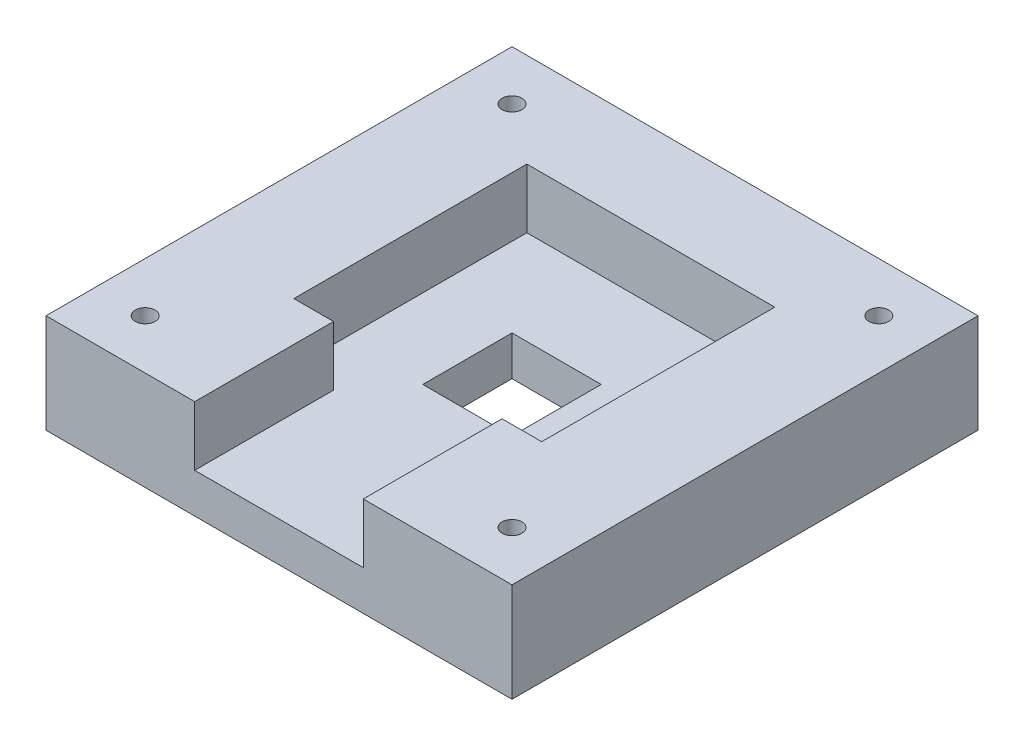
SolidWorks part; units mm, degrees
ref_plane "Front Plane" through (0, 0, 0) normal (0, 0, 1) x (1, 0, 0)
ref_plane "Top Plane" through (0, 0, 0) normal (0, 1, 0) x (1, 0, 0)
ref_plane "Right Plane" through (0, 0, 0) normal (1, 0, 0) x (0, 0, -1)
sketch "Sketch1" plane through (0, 0, 0) normal (0, 1, 0) x (1, 0, 0)
  line L1 (0, 0) -> (47, 0)
  line L2 (0, 0) -> (0, -47)
  line L3 (0, -47) -> (47, -47)
  line L4 (47, 0) -> (47, -47)
  dimension "D1" = 47
  dimension "D2" = 47
extrude "Boss-Extrude1" add sketch "Sketch1" along normal blind 10
sketch "Sketch2" plane through (0, 0, 0) normal (0, -1, 0) x (-1, 0, 0)
  line L0 (0, -47) -> (-47, -47) construction
  line L1 (-28, -19) -> (-19, -19)
  line L2 (-28, -19) -> (-28, -28)
  line L3 (-28, -28) -> (-19, -28)
  line L4 (-19, -19) -> (-19, -28)
  line L5 (-47, -47) -> (-47, 0) construction
  dimension "D1" = 9
  dimension "D2" = 9
  dimension "D3" = 19
  dimension "D4" = 19
extrude "Cut-Extrude1" cut sketch "Sketch2" against normal blind 4
sketch "Sketch5" plane through (0, 0, 0) normal (0, -1, 0) x (-1, 0, 0)
  line L0 (-28, -28) -> (-19, -28) construction
  line L1 (-36, -9.5) -> (-11, -9.5)
  line L2 (-36, -9.5) -> (-36, -33)
  line L3 (-36, -33) -> (-11, -33)
  line L4 (-11, -9.5) -> (-11, -33)
  line L5 (-19, -28) -> (-19, -19) construction
  line L6 (0, -47) -> (-47, -47) construction
  line L7 (-32, -33) -> (-15, -33)
  line L8 (-32, -33) -> (-32, -47)
  line L9 (-32, -47) -> (-15, -47)
  line L10 (-15, -33) -> (-15, -47)
  dimension "D1" = 5
  dimension "D2" = 8
  dimension "D3" = 23.5
  dimension "D4" = 25
  dimension "D5" = 4
  dimension "D6" = 4
sketch3d "3DSketch1"
  line L0 (36, 0, 9.5) -> (36, 0, 33) construction
  line L1 (36, 4, 9.5) -> (11, 4, 9.5)
  line L2 (36, 4, 9.5) -> (36, 4, 33)
  line L3 (36, 4, 33) -> (11, 4, 33)
  line L4 (11, 4, 9.5) -> (11, 4, 33)
  line L5 (32, 4, 33) -> (15, 4, 33)
  line L6 (32, 4, 33) -> (32, 4, 47)
  line L7 (32, 4, 47) -> (15, 4, 47)
  line L8 (15, 4, 33) -> (15, 4, 47)
  line L9 (11, 0, 9.5) -> (11, 0, 33) construction
  line L10 (36, 0, 33) -> (11, 0, 33) construction
  line L11 (32, 0, 33) -> (32, 0, 47) construction
  line L12 (15, 0, 33) -> (15, 0, 47) construction
  line L13 (32, 0, 47) -> (15, 0, 47) construction
  point P8 (36, 4, 21.25)
  dimension "D1" = 4
  dimension "D2" = 25
  dimension "D3" = 23.5
  dimension "D4" = 4
  dimension "D5" = 4
  dimension "D6" = 4
  dimension "D7" = 4
  dimension "D8" = 4
  dimension "D9" = 4
extrude "Cut-Extrude3" cut sketch "3DSketch1" along direction (0, 1, 0) on the side against the normal through all contours L1 L4 L3 L2 | L6 L7 L8 L5
sketch "Sketch8" plane through (0, 0, 0) normal (0, -1, 0) x (1, 0, 0)
  line L0 (47, 0) -> (0, 0) construction
  line L1 (47, 47) -> (47, 0) construction
  line L2 (0, 0) -> (0, 47) construction
  line L3 (0, 47) -> (47, 47) construction
  circle A0 centre (42, 5) radius 1
  circle A1 centre (5, 5) radius 1
  circle A2 centre (5, 42) radius 1
  circle A3 centre (42, 42) radius 1
  dimension "D1" = 2
  dimension "D2" = 2
  dimension "D3" = 2
  dimension "D4" = 2
  dimension "D5" = 5
  dimension "D6" = 5
  dimension "D7" = 5
  dimension "D8" = 5
  dimension "D9" = 5
  dimension "D10" = 5
  dimension "D11" = 5
  dimension "D12" = 5
extrude "Cut-Extrude4" cut sketch "Sketch8" against normal through all
